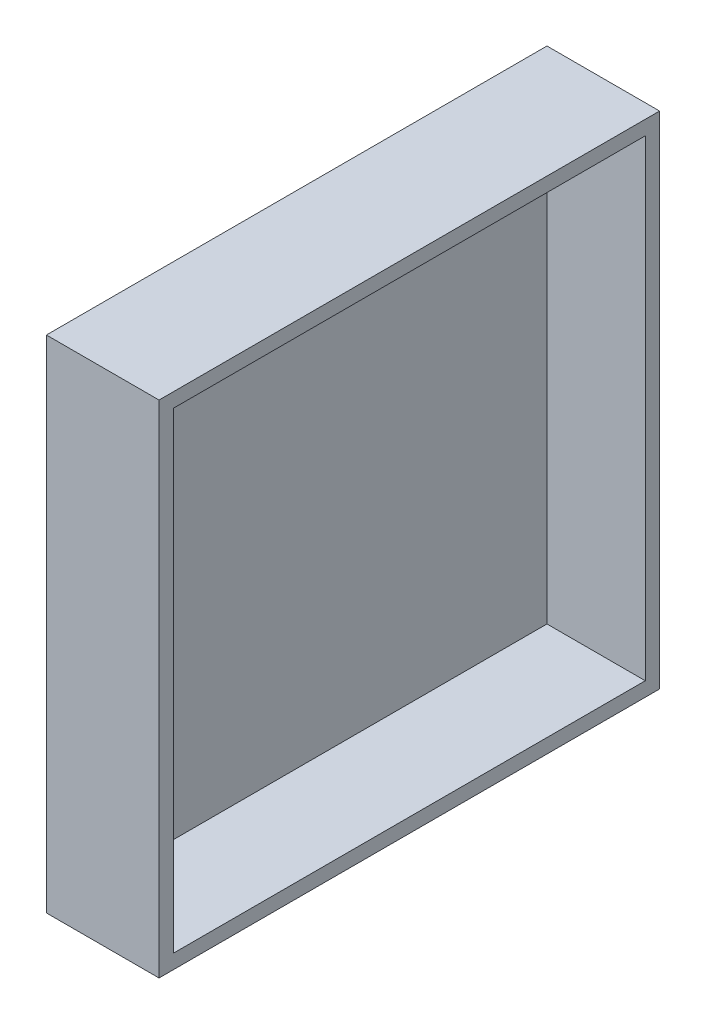
SolidWorks part; units mm, degrees
ref_plane "Front Plane" through (0, 0, 0) normal (0, 0, 1) x (1, 0, 0)
ref_plane "Top Plane" through (0, 0, 0) normal (0, 1, 0) x (1, 0, 0)
ref_plane "Right Plane" through (0, 0, 0) normal (1, 0, 0) x (0, 0, -1)
sketch "Sketch1" plane through (0, 0, 0) normal (1, 0, 0) x (0, 0, -1)
  line L0 (-140, 0) -> (140, 0) construction
  line L1 (140, 140) -> (-140, 140)
  line L2 (140, 140) -> (140, -140)
  line L3 (140, -140) -> (-140, -140)
  line L4 (-140, 140) -> (-140, -140)
  line L7 (0, 140) -> (0, -140) construction
  point P0 (0, 0)
  dimension "D1" = 280
  dimension "D2" = 280
extrude "Boss-Extrude1" add sketch "Sketch1" along normal blind 63
sketch "Sketch2" plane through (63, 0, 0) normal (1, 0, 0) x (0, 0, -1)
  line L0 (140, 140) -> (-140, 140) construction
  line L1 (132, 132) -> (-132, 132)
  line L2 (132, 132) -> (132, -132)
  line L3 (132, -132) -> (-132, -132)
  line L4 (-132, 132) -> (-132, -132)
  line L5 (132, 132) -> (-132, -132) construction
  line L6 (132, -132) -> (-132, 132) construction
  line L7 (-140, 140) -> (-140, -140) construction
  line L8 (140, -140) -> (140, 140) construction
  line L9 (-140, -140) -> (140, -140) construction
  point P0 (0, 0)
  dimension "D1" = 8
  dimension "D2" = 8
  dimension "D3" = 8
  dimension "D4" = 8
extrude "Cut-Extrude1" cut sketch "Sketch2" against normal blind 55
sketch "Sketch4" plane through (8, 0, 0) normal (1, 0, 0) x (0, 0, -1)
  line L0 (132, 132) -> (-132, 132) construction
  line L1 (132, -132) -> (132, 132) construction
  circle A0 centre (107, 107) radius 15
  dimension "D1" = 30
  dimension "D3" = 25
  dimension "D2" = 25
extrude "Cut-Extrude2" cut sketch "Sketch4" against normal blind 55
